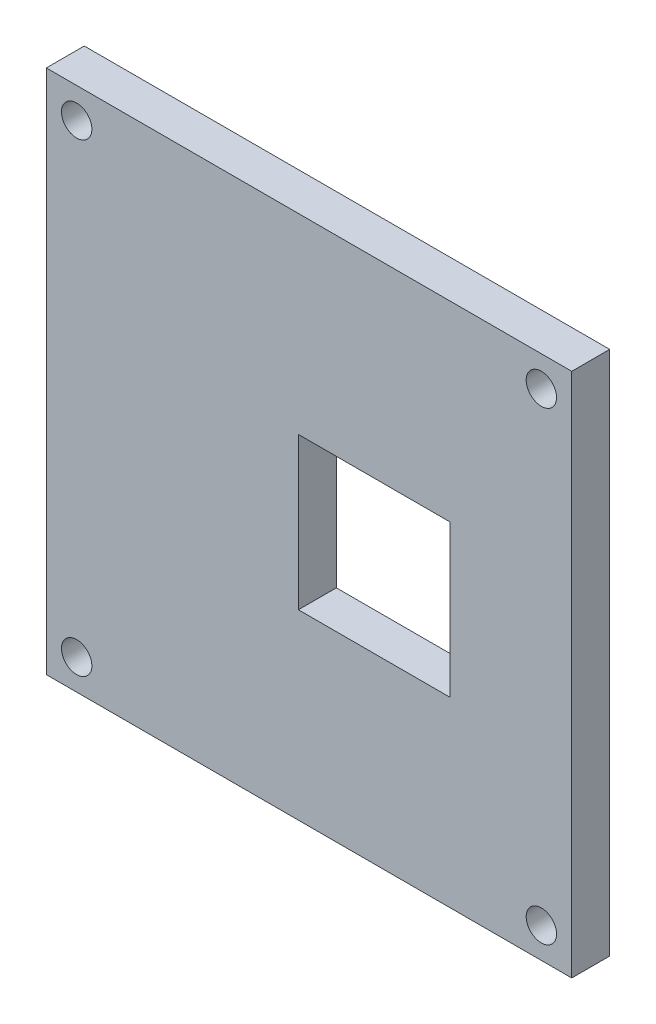
SolidWorks part; units mm, degrees
ref_plane "Front Plane" through (0, 0, 0) normal (0, 0, 1) x (1, 0, 0)
ref_plane "Top Plane" through (0, 0, 0) normal (0, 1, 0) x (1, 0, 0)
ref_plane "Right Plane" through (0, 0, 0) normal (1, 0, 0) x (0, 0, -1)
sketch "Sketch1" plane through (0, 0, 0) normal (0, 0, 1) x (1, 0, 0)
  line L0 (2.54, 41.402) -> (41.402, 41.402) construction
  line L1 (0, 0) -> (43.942, 0)
  line L2 (0, 0) -> (0, 43.942)
  line L3 (0, 43.942) -> (43.942, 43.942)
  line L4 (43.942, 0) -> (43.942, 43.942)
  line L5 (41.402, 2.54) -> (41.402, 41.402) construction
  line L6 (2.54, 2.54) -> (41.402, 2.54) construction
  line L7 (2.54, 2.54) -> (2.54, 41.402) construction
  line L9 (21.082, 15.24) -> (33.782, 15.24)
  line L10 (21.082, 15.24) -> (21.082, 27.94)
  line L11 (21.082, 27.94) -> (33.782, 27.94)
  line L12 (33.782, 15.24) -> (33.782, 27.94)
  line L13 (21.082, 15.24) -> (33.782, 27.94) construction
  line L14 (21.082, 27.94) -> (33.782, 15.24) construction
  circle A0 centre (2.54, 41.402) radius 1.27
  circle A1 centre (41.402, 41.402) radius 1.27
  circle A2 centre (41.402, 2.54) radius 1.27
  circle A3 centre (2.54, 2.54) radius 1.27
  point P13 (27.432, 21.59)
  dimension "D3" = 2.54
  dimension "D1" = 43.942
  dimension "D4" = 12.7
  dimension "D5" = 7.62
  dimension "D6" = 12.7
  dimension "D2" = 2.54
extrude "Boss-Extrude1" add sketch "Sketch1" along normal blind 3.175
